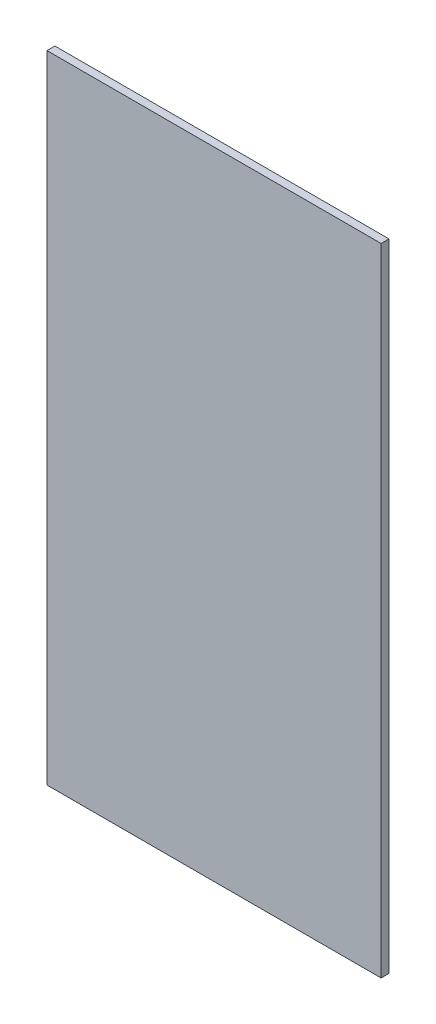
SolidWorks part; units mm, degrees
ref_plane "Front Plane" through (0, 0, 0) normal (0, 0, 1) x (1, 0, 0)
ref_plane "Top Plane" through (0, 0, 0) normal (0, 1, 0) x (1, 0, 0)
ref_plane "Right Plane" through (0, 0, 0) normal (1, 0, 0) x (0, 0, -1)
sketch "Sketch1" plane through (0, 0, 0) normal (0, 0, 1) x (1, 0, 0)
  line L1 (63.373, -120.65) -> (-63.373, -120.65)
  line L2 (63.373, -120.65) -> (63.373, 120.65)
  line L3 (63.373, 120.65) -> (-63.373, 120.65)
  line L4 (-63.373, -120.65) -> (-63.373, 120.65)
  line L5 (63.373, -120.65) -> (-63.373, 120.65) construction
  line L6 (63.373, 120.65) -> (-63.373, -120.65) construction
  point P0 (0, 0)
  dimension "D1" = 241.3
  dimension "D2" = 126.746
extrude "Boss-Extrude1" add sketch "Sketch1" along normal blind 2.9972
